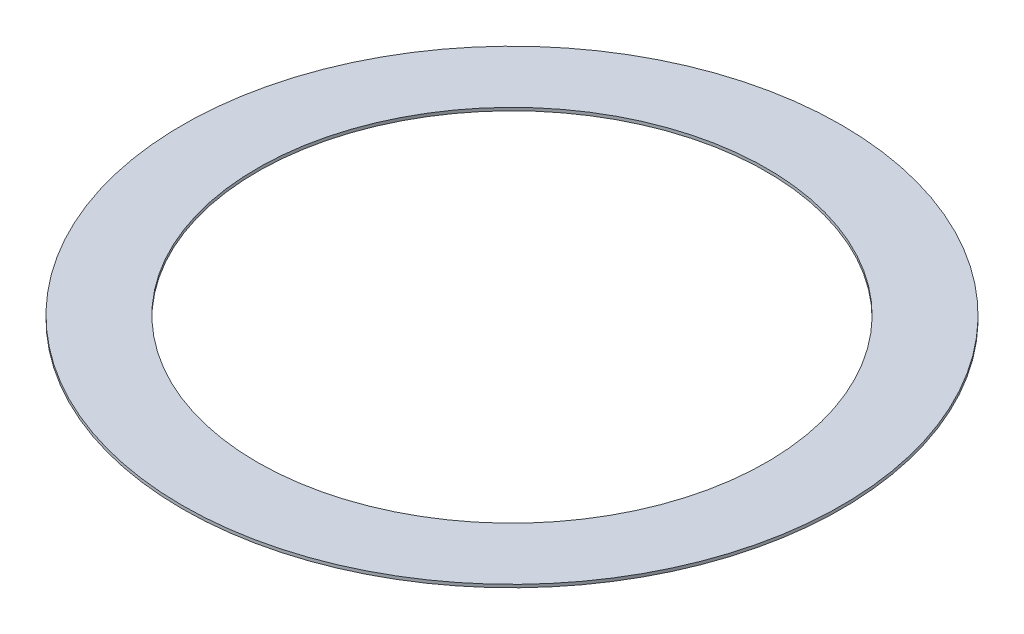
SolidWorks part; units mm, degrees
ref_plane "前视基准面" through (0, 0, 0) normal (0, 0, 1) x (1, 0, 0)
ref_plane "上视基准面" through (0, 0, 0) normal (0, 1, 0) x (1, 0, 0)
ref_plane "右视基准面" through (0, 0, 0) normal (1, 0, 0) x (0, 0, -1)
other "Configuration Table"
sketch "草图1" plane through (0, 0, 0) normal (0, 1, 0) x (1, 0, 0)
  circle A0 centre (0, 0) radius 8.5
  circle A1 centre (0, 0) radius 11
  dimension "D1" = 17
  dimension "D2" = 22
extrude "凸台-拉伸1" add sketch "草图1" along normal blind 0.1 contours A1
